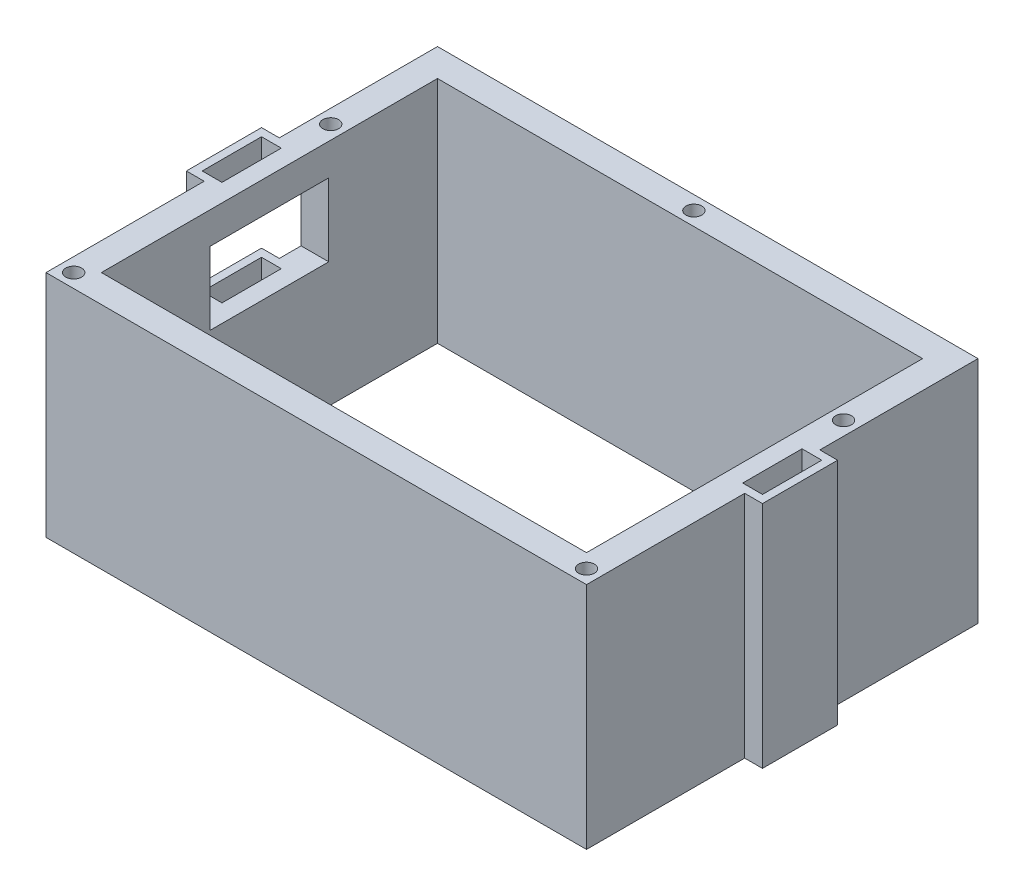
SolidWorks part; units mm, degrees
ref_plane "Front Plane" through (0, 0, 0) normal (0, 0, 1) x (1, 0, 0)
ref_plane "Top Plane" through (0, 0, 0) normal (0, 1, 0) x (1, 0, 0)
ref_plane "Right Plane" through (0, 0, 0) normal (1, 0, 0) x (0, 0, -1)
sketch "Sketch1" plane through (0, 0, 0) normal (0, 1, 0) x (1, 0, 0)
  line L0 (-68.342, -49.5) -> (-68.342, 49.5)
  line L1 (-61.342, -42.5) -> (61.342, -42.5)
  line L2 (-61.342, -42.5) -> (-61.342, 42.5)
  line L3 (-61.342, 42.5) -> (61.342, 42.5)
  line L4 (61.342, -42.5) -> (61.342, 42.5)
  line L5 (-61.342, -42.5) -> (61.342, 42.5) construction
  line L6 (-61.342, 42.5) -> (61.342, -42.5) construction
  line L7 (-68.342, 49.5) -> (68.342, 49.5)
  line L8 (68.342, -49.5) -> (68.342, 49.5)
  line L9 (-68.342, -49.5) -> (68.342, -49.5)
  line L10 (-68.342, 0) -> (-65.842, 0) construction
  line L11 (-65.842, 0) -> (-65.842, 7.5) construction
  line L12 (0, 0) -> (0, 42.5) construction
  line L13 (-70.842, -7.5) -> (-65.842, -7.5)
  line L14 (-70.842, -7.5) -> (-70.842, 7.5)
  line L15 (-70.842, 7.5) -> (-65.842, 7.5)
  line L16 (-65.842, -7.5) -> (-65.842, 7.5)
  line L17 (-70.842, -7.5) -> (-65.842, 7.5) construction
  line L18 (-70.842, 7.5) -> (-65.842, -7.5) construction
  line L19 (-72.842, -9.5) -> (-72.842, 9.5)
  line L20 (-72.842, 9.5) -> (-63.842, 9.5)
  line L21 (-63.842, -9.5) -> (-63.842, 9.5)
  line L22 (-72.842, -9.5) -> (-63.842, -9.5)
  line L23 (72.842, -9.5) -> (63.842, -9.5)
  line L24 (63.842, -9.5) -> (63.842, 9.5)
  line L25 (72.842, 9.5) -> (63.842, 9.5)
  line L26 (72.842, -9.5) -> (72.842, 9.5)
  line L27 (70.842, 7.5) -> (65.842, 7.5)
  line L28 (65.842, -7.5) -> (65.842, 7.5)
  line L29 (70.842, -7.5) -> (65.842, -7.5)
  line L30 (70.842, -7.5) -> (70.842, 7.5)
  point P0 (0, 0)
  dimension "D2" = 2
  dimension "D1" = 7
extrude "Boss-Extrude1" add sketch "Sketch1" along normal blind 58 contours L25 L8 L7 L0 L20 L21 L22 L9 L23 L24 L4 L1 L2 L3 | L8 L29 L28 L27 L25 L24 L23 | L30 L29 L8 L23 L26 L25 L27 | L19 L22 L0 L13 L14 L15 L20 | L0 L22 L21 L20 L15 L16 L13
ref_plane "Plane1" through (-72.842, 0, 0) normal (-1, 0, 0) x (0, 0, 1)
sketch "Sketch2" plane through (-72.842, 0, 0) normal (-1, 0, 0) x (0, 0, 1)
  line L0 (0, 0) -> (0, 40.801) construction
  line L2 (-15, 31.602) -> (15, 31.602)
  line L3 (-15, 31.602) -> (-15, 50)
  line L4 (-15, 50) -> (15, 50)
  line L5 (15, 31.602) -> (15, 50)
  line L6 (-15, 31.602) -> (15, 50) construction
  line L7 (-15, 50) -> (15, 31.602) construction
extrude "Cut-Extrude1" cut sketch "Sketch2" against normal blind 11.5
sketch "Sketch3" plane through (0, 0, 0) normal (0, 1, 0) x (1, 0, 0)
  line L0 (0, 0) -> (13.5974, 0) construction
  line L1 (0, 0) -> (0, -8.9797) construction
  line L2 (64.8156, -49.5) -> (64.8156, -46) construction
  line L3 (-68.342, -49.5) -> (68.342, -49.5) construction
  line L4 (68.342, -46) -> (64.842, -46) construction
  line L5 (68.342, -49.5) -> (68.342, -9.5) construction
  circle A0 centre (64.842, -46) radius 2
  circle A1 centre (64.842, 46) radius 2
  circle A2 centre (-64.842, 46) radius 2
  circle A3 centre (-64.842, -46) radius 2
extrude "Cut-Extrude3" cut sketch "Sketch3" against normal blind 0.0001 and the other way blind 5.7
ref_plane "Plane2" through (0, 58, 0) normal (0, 1, 0) x (1, 0, 0)
sketch "Sketch5" plane through (0, 58, 0) normal (0, 1, 0) x (1, 0, 0)
  line L0 (-64.9751, -49.5) -> (-64.9751, -46) construction
  line L1 (-68.342, -49.5) -> (68.342, -49.5) construction
  line L2 (-68.342, -46) -> (-64.842, -46) construction
  line L3 (-68.342, -49.5) -> (-68.342, -9.5) construction
  line L4 (0, -55) -> (0, 55) construction
  line L5 (-55, 0) -> (55, 0) construction
  line L6 (-64.9751, -46) -> (64.842, -46) construction
  line L7 (-64.842, -46) -> (-64.842, 46) construction
  line L8 (64.842, -46) -> (64.842, 19) construction
  circle A0 centre (-64.842, -46) radius 2
  circle A1 centre (64.842, -46) radius 2
  circle A4 centre (64.842, 19) radius 2
  circle A5 centre (-64.842, 19) radius 2
  circle A6 centre (0, 46) radius 2
extrude "Cut-Extrude4" cut sketch "Sketch5" against normal blind 5.7
